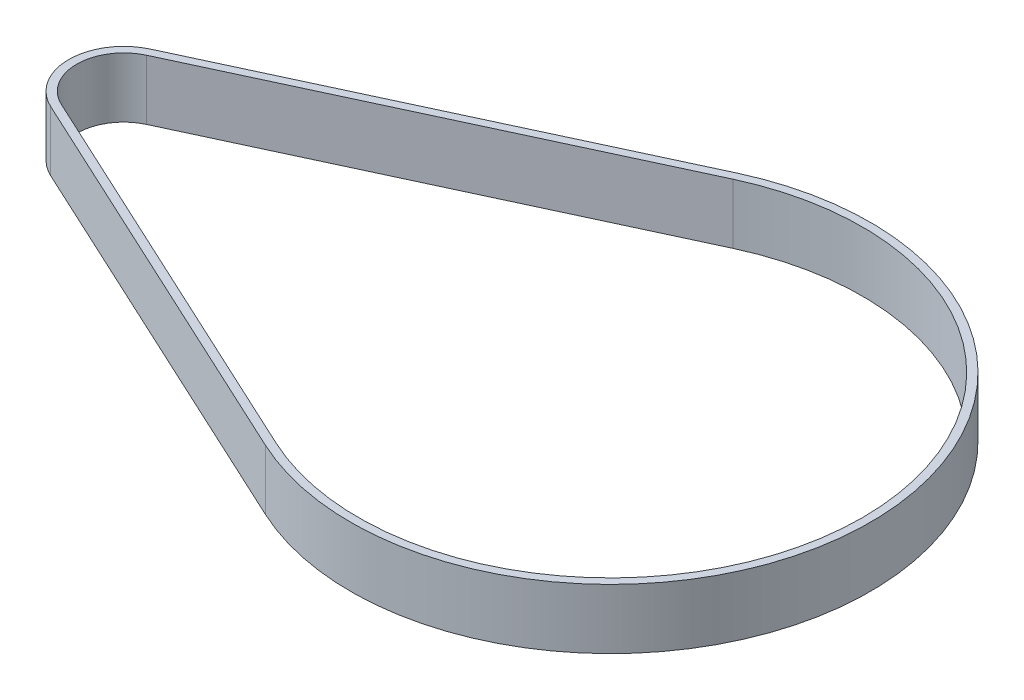
SolidWorks part; units mm, degrees
ref_plane "Front Plane" through (0, 0, 0) normal (0, 0, 1) x (1, 0, 0)
ref_plane "Top Plane" through (0, 0, 0) normal (0, 1, 0) x (1, 0, 0)
ref_plane "Right Plane" through (0, 0, 0) normal (1, 0, 0) x (0, 0, -1)
sketch "Sketch1" plane through (0, 0, 0) normal (0, 1, 0) x (1, 0, 0)
  line L0 (-50.7034, 4.2633) -> (-10.6117, 22.8678)
  line L1 (-50.7034, -4.2633) -> (-10.6117, -22.8678)
  line L2 (-51.0401, 4.989) -> (-10.9485, 23.5934)
  line L3 (-51.0401, -4.989) -> (-10.9485, -23.5934)
  arc A0 (-10.6117, -22.8678) -> (-10.6117, 22.8678) centre (0, 0) ccw
  arc A1 (-50.7034, 4.2633) -> (-50.7034, -4.2633) centre (-48.725, 0) ccw
  arc A2 (-10.9485, -23.5934) -> (-10.9485, 23.5934) centre (0, 0) ccw
  arc A3 (-51.0401, 4.989) -> (-51.0401, -4.989) centre (-48.725, 0) ccw
  dimension "D1" = 9.4
  dimension "D2" = 50.42
  dimension "D3" = 48.725
  dimension "D4" = 0.8
extrude "Boss-Extrude1" add sketch "Sketch1" along normal blind 6
equation "\"center distance\"=48.725"
equation "\"D3@Sketch1\"=\"center distance\""
equation "\"small dia\"=9.4"
equation "\"D1@Sketch1\"=\"small dia\""
equation "\"large dia\"=50.42"
equation "\"D2@Sketch1\"=\"large dia\""
equation "\"belt thickness\"=0.8"
equation "\"D4@Sketch1\"=\"belt thickness\""
